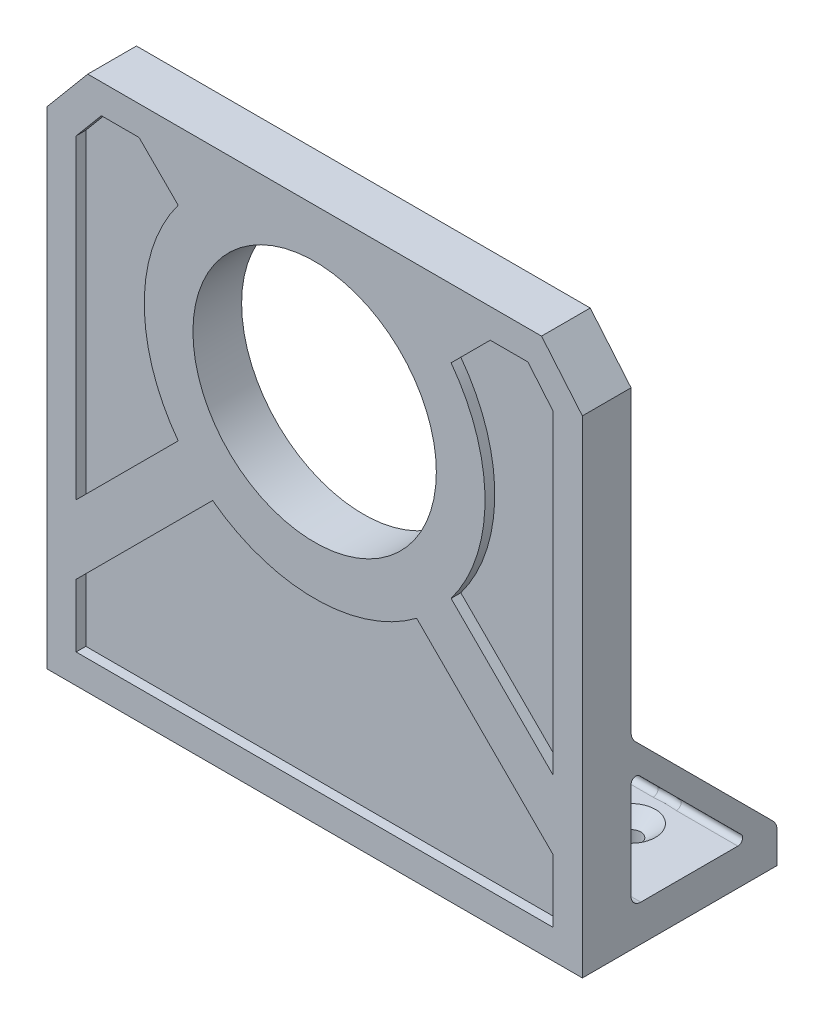
SolidWorks part; units mm, degrees
ref_plane "Front Plane" through (0, 0, 0) normal (0, 0, 1) x (1, 0, 0)
ref_plane "Top Plane" through (0, 0, 0) normal (0, 1, 0) x (1, 0, 0)
ref_plane "Right Plane" through (0, 0, 0) normal (1, 0, 0) x (0, 0, -1)
sketch "Sketch1" plane through (0, 0, 0) normal (0, 1, 0) x (1, 0, 0)
  line L1 (0, 0) -> (110, 0)
  line L2 (0, 0) -> (0, 10)
  line L3 (0, 10) -> (110, 10)
  line L4 (110, 0) -> (110, 10)
  dimension "D1" = 110
  dimension "D2" = 10
extrude "Boss-Extrude1" add sketch "Sketch1" along normal blind 110
sketch "Sketch2" plane through (0, 0, -10) normal (0, 0, -1) x (-1, 0, 0)
  line L0 (0, 110) -> (0, 0) construction
  line L1 (-110, 0) -> (-80, 0)
  line L2 (-110, 0) -> (-110, 7.5)
  line L3 (-110, 7.5) -> (-80, 7.5)
  line L4 (0, 0) -> (0, 7.5)
  line L5 (-55, 10) -> (-55, 0) construction
  line L6 (-30, 7.5) -> (-30, 0)
  line L7 (-80, 7.5) -> (-80, 0)
  line L8 (-30, 7.5) -> (0, 7.5)
  line L9 (-30, 0) -> (0, 0)
  dimension "D1" = 7.5
  dimension "D2" = 30
extrude "Boss-Extrude2" add sketch "Sketch2" along normal blind 30
sketch "Sketch3" plane through (110, 0, 0) normal (1, 0, 0) x (0, 0, -1)
  line L1 (10, 110) -> (10, 7.5) construction
  line L4 (10, 37.5) -> (40, 7.5)
  dimension "D1" = 30
extrude "Extrude-Thin1" add sketch "Sketch3" against normal blind 30 thin
sketch "Sketch4" plane through (0, 7.5, 0) normal (0, 1, 0) x (1, 0, 0)
  line L0 (95, 40) -> (95, 10) construction
  line L1 (80, 40) -> (110, 40) construction
  line L2 (110, 10) -> (0, 10) construction
  line L3 (80, 25) -> (110, 25) construction
  line L4 (80, 10) -> (80, 40) construction
  line L5 (110, 10) -> (110, 40) construction
  line L6 (55, 10) -> (55, 40) construction
  circle A0 centre (95, 25) radius 8
  circle A1 centre (15, 25) radius 8
  dimension "D1" = 16
extrude "Cut-Extrude1" cut sketch "Sketch4" along normal blind 30
sketch "Sketch5" plane through (0, 0, -10) normal (0, 0, -1) x (-1, 0, 0)
  line L0 (-55, 110) -> (-55, 0) construction
  line L1 (-110, 110) -> (0, 110) construction
  line L2 (-80, 0) -> (-30, 0) construction
  line L4 (-55, 0) -> (-47.7918, 0)
  line L5 (-55, 0) -> (-55, 110)
  line L6 (-55, 110) -> (-47.7918, 110)
  line L7 (-47.7918, 0) -> (-47.7918, 110)
extrude "Boss-Extrude4" add sketch "Sketch5" along normal blind 30
mirror "Mirror1" about plane through (55, 0, -40) normal (-1, 0, 0) of "Extrude-Thin1"
mirror "Mirror2" about plane through (55, 0, -40) normal (-1, 0, 0) of "Cut-Extrude1"
sketch "Sketch7" plane through (0, 0, -40) normal (0, 0, -1) x (-1, 0, 0)
  line L4 (-47.7918, 110) -> (-55, 110)
  line L5 (-55, 110) -> (-55, 0)
  line L6 (-55, 0) -> (-47.7918, 0)
  line L7 (-47.7918, 0) -> (-47.7918, 110)
  line L8 (-47.7918, 110) -> (-55, 110)
  line L9 (-55, 110) -> (-55, 0)
  line L10 (-55, 0) -> (-47.7918, 0)
  line L11 (-47.7918, 0) -> (-47.7918, 110)
  dimension "D1" = 0
extrude "Cut-Extrude2" cut sketch "Sketch7" against normal blind 30
sketch "Sketch8" plane through (0, 0, 0) normal (0, 0, 1) x (1, 0, 0)
  line L0 (0, 75) -> (110, 75) construction
  line L3 (55, 110) -> (55, 0) construction
  line L4 (0, 110) -> (110, 110) construction
  line L5 (0, 0) -> (110, 0) construction
  line L6 (0, 110) -> (0, 0) construction
  line L7 (110, 110) -> (110, 0) construction
  circle A2 centre (55, 75) radius 25
  dimension "D1" = 75
  dimension "D2" = 50
sketch "Sketch9" plane through (0, 7.5, 0) normal (0, 1, 0) x (1, 0, 0)
  line L0 (55, 10) -> (55, 43.4774) construction
  line L1 (110, 10) -> (0, 10) construction
  line L2 (80, 25) -> (110, 25) construction
  line L3 (80, 10) -> (80, 40) construction
  line L4 (110, 10) -> (110, 40) construction
  line L5 (30, 25) -> (0, 25) construction
  line L6 (95, 40) -> (95, 10) construction
  line L7 (80, 40) -> (110, 40) construction
  line L8 (80, 10) -> (110, 10) construction
  line L9 (15, 40) -> (15, 10) construction
  circle A0 centre (95, 25) radius 2
  circle A1 centre (15, 25) radius 2
  dimension "D1" = 4
extrude "Cut-Extrude5" cut sketch "Sketch9" against normal blind 30
chamfer "Chamfer1" distance 3 angle 40 2 edges at (15, 7.5, -27) (95, 7.5, -23)
sketch "Sketch10" plane through (0, 0, 0) normal (0, -1, 0) x (1, 0, 0)
  line L0 (55, 0) -> (55, -41.2097) construction
  line L1 (80, 0) -> (30, 0) construction
  line L2 (4, -36) -> (4, -4)
  line L3 (106, -36) -> (84, -36)
  line L4 (106, -36) -> (106, -4)
  line L5 (106, -4) -> (84, -4)
  line L6 (84, -36) -> (84, -4)
  line L7 (4, -36) -> (26, -36)
  line L8 (26, -36) -> (26, -4)
  line L9 (4, -4) -> (26, -4)
  line L10 (110, -40) -> (80, -40) construction
  line L11 (110, 0) -> (110, -40) construction
  line L12 (80, -40) -> (80, -10) construction
  line L13 (0, 0) -> (110, 0) construction
  dimension "D1" = 4
  dimension "D2" = 4
  dimension "D3" = 4
  dimension "D4" = 4
extrude "Cut-Extrude6" cut sketch "Sketch10" against normal blind 2
extrude "Cut-Extrude7" cut sketch "Sketch8" against normal blind 10
chamfer "Chamfer2" distance 10 angle 40 2 edges at (0, 110, -5) (110, 110, -5)
sketch "Sketch11" plane through (0, 0, 0) normal (0, 0, 1) x (1, 0, 0)
  line L0 (55, 100) -> (55, 50) construction
  circle A0 centre (55, 75) radius 25 construction
fillet "Fillet1" radius 1 2 edges at (95, 7.5, -34.3431) (15, 7.5, -34.3431)
fillet "Fillet2" radius 1 2 edges at (15, 31.8431, -10) (95, 31.8431, -10)
fillet "Fillet3" radius 2 2 edges at (15, 7.5, -10) (95, 7.5, -10)
fillet "Fillet4" radius 3 4 edges at (15, 37.5, -10) (95, 37.5, -10) (95, 7.5, -40) (15, 7.5, -40)
sketch "Sketch12" plane through (0, 0, 0) normal (0, 0, 1) x (1, 0, 0)
  line L1 (55, 75) -> (72.6777, 57.3223) construction
  line L2 (72.6777, 57.3223) -> (110, 20) construction
  line L3 (110, 100) -> (110, 0) construction
  line L4 (55, 75) -> (20, 110) construction
  line L5 (8.391, 110) -> (101.609, 110) construction
  line L6 (110, 130) -> (0, 20) construction
  line L7 (0, 100) -> (0, 0) construction
  line L8 (155.2204, -25.2204) -> (-25.0297, 155.0297) construction
  line L9 (150.995, 170.995) -> (-51.2111, -31.2111) construction
  line L10 (158.7559, -21.6848) -> (-21.4942, 158.5652)
  line L11 (147.4595, 174.5306) -> (-54.7467, -27.6756)
  line L12 (151.6848, -28.7559) -> (-28.5652, 151.4942)
  line L13 (154.5306, 167.4595) -> (-47.6756, -34.7467)
  line L14 (6, 97.8162) -> (6, 6)
  line L15 (6, 6) -> (104, 6)
  line L16 (104, 6) -> (104, 97.8162)
  line L17 (104, 97.8162) -> (98.8112, 104)
  line L18 (98.8112, 104) -> (11.1888, 104)
  line L19 (11.1888, 104) -> (6, 97.8162)
  line L20 (101.609, 110) -> (8.391, 110)
  line L21 (8.391, 110) -> (0, 100)
  line L22 (0, 100) -> (0, 0)
  line L23 (0, 0) -> (110, 0)
  line L24 (110, 0) -> (110, 100)
  line L25 (110, 100) -> (101.609, 110)
  line L26 (101.609, 110) -> (8.391, 110)
  line L27 (8.391, 110) -> (0, 100)
  line L28 (0, 100) -> (0, 0)
  line L29 (0, 0) -> (110, 0)
  line L30 (110, 0) -> (110, 100)
  line L31 (110, 100) -> (101.609, 110)
  arc A0 (55, 50) -> (72.6777, 57.3223) centre (55, 75) ccw construction
  circle A1 centre (55, 75) radius 25 construction
  circle A2 centre (55, 75) radius 25
  circle A3 centre (55, 75) radius 35
  dimension "D6" = 10
  dimension "D1" = 45
  dimension "D2" = 5
  dimension "D3" = 5
  dimension "D4" = 0
  dimension "D5" = 6
extrude "Cut-Extrude8" cut sketch "Sketch12" against normal blind 2 contours A3 L12 L18 L19 L14 L11 | A3 L13 L14 L15 L16 L12 | A3 L10 L16 L17 L18 L13
sketch "Sketch17" plane through (0, 0, -10) normal (0, 0, -1) x (-1, 0, 0)
  line L7 (-127.0317, 114.9278) -> (76.8928, 1.8906) construction
  line L8 (-151.809, 21.3379) -> (45.8333, 130.8928) construction
  line L9 (-181.0043, 75) -> (87.352, 75) construction
  line L10 (-149.8698, 17.8394) -> (47.7725, 127.3943)
  line L11 (-128.9709, 111.4293) -> (74.9536, -1.6079)
  line L12 (-153.7483, 24.8364) -> (43.894, 134.3913)
  line L13 (-125.0924, 118.4263) -> (78.832, 5.3891)
  line L14 (-104, 44.7426) -> (-80, 44.7426)
  line L15 (-30, 44.7426) -> (-6, 44.7426)
  line L16 (-6, 44.7426) -> (-6, 97.8162)
  line L17 (-6, 97.8162) -> (-11.1888, 104)
  line L18 (-11.1888, 104) -> (-98.8112, 104)
  line L19 (-98.8112, 104) -> (-104, 97.8162)
  line L20 (-104, 97.8162) -> (-104, 44.7426)
  line L21 (-104, 44.7426) -> (-80, 44.7426)
  line L22 (-80, 44.7426) -> (-6, 44.7426)
  line L23 (-6, 44.7426) -> (-6, 97.8162)
  line L24 (-6, 97.8162) -> (-11.1888, 104)
  line L25 (-11.1888, 104) -> (-98.8112, 104)
  line L26 (-98.8112, 104) -> (-104, 97.8162)
  line L27 (-104, 97.8162) -> (-104, 44.7426)
  circle A2 centre (-55, 75) radius 31
  circle A3 centre (-55, 75) radius 31
  dimension "D3" = 29
  dimension "D4" = 29
  dimension "D1" = 6
  dimension "D2" = 6
  dimension "D5" = 4
  dimension "D6" = 4
extrude "Cut-Extrude9" cut sketch "Sketch17" against normal blind 2 contours A3 L11 L27 L12 | A3 L25 L26 L13 | A3 L12 L24 L25 | A3 L13 L23 L10 | A3 L22 L11 | A3 L10 L21 L22
